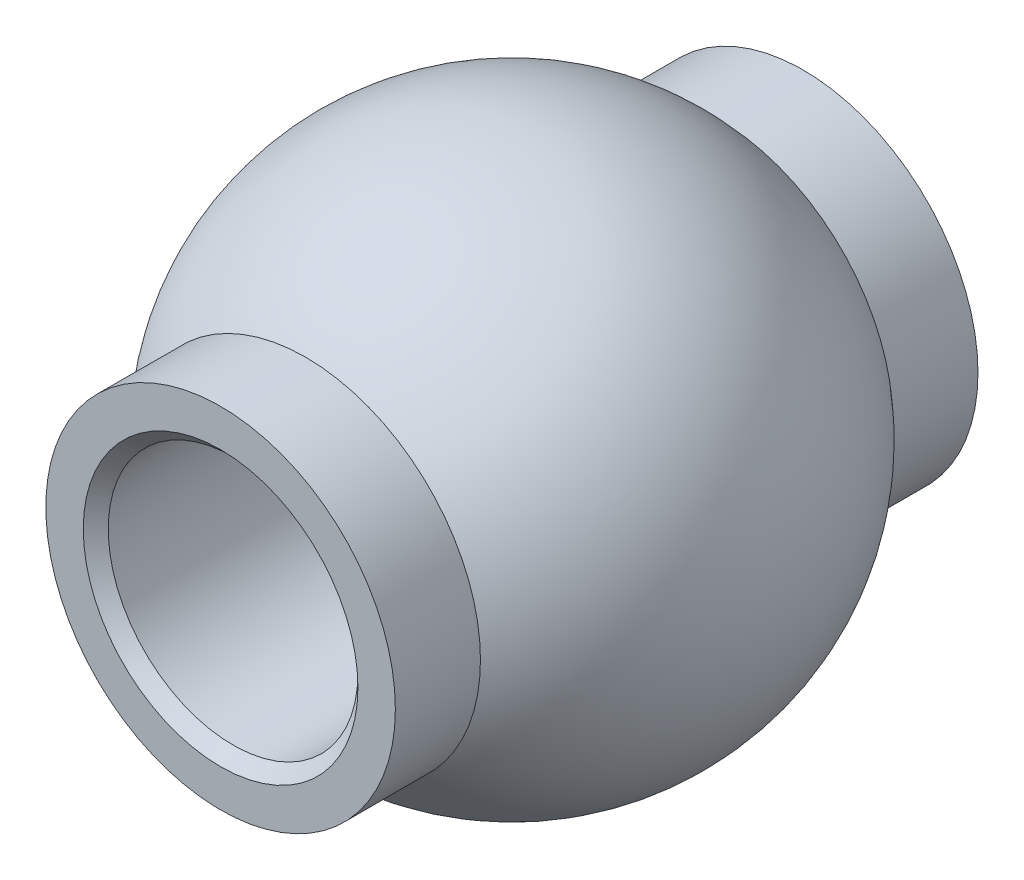
SolidWorks part; units mm, degrees
ref_plane "Front" through (0, 0, 0) normal (0, 0, 1) x (1, 0, 0)
ref_plane "Top" through (0, 0, 0) normal (0, 1, 0) x (1, 0, 0)
ref_plane "Right" through (0, 0, 0) normal (1, 0, 0) x (0, 0, -1)
sketch "Sketch1" plane through (0, 0, 0) normal (0, 0, 1) x (1, 0, 0)
  line L0 (0, 0) -> (0, -26.9875) construction
  line L1 (0, -26.9875) -> (4.7625, -26.9875) construction
  line L2 (4.7625, -26.9875) -> (4.7625, 0) construction
  line L3 (4.7625, 0) -> (0, 0) construction
  line L5 (0, 41.275) -> (0, 0) construction
  line L6 (0, 41.275) -> (14.2875, 41.275) construction
  line L7 (14.2875, 41.275) -> (14.2875, 26.9875) construction
  line L8 (-4.7625, -26.9875) -> (-4.7625, 0) construction
  line L9 (-8.7249, -26.9875) -> (8.7249, -26.9875) construction
  line L10 (8.7249, -26.9875) -> (8.7249, 10.0476) construction
  line L11 (-8.7249, -26.9875) -> (-8.7249, 10.0476) construction
  line L12 (4.8771, -26.9214) -> (4.8771, -27.9797) construction
  line L13 (4.8771, -27.9797) -> (3.9605, -27.4505) construction
  line L14 (3.9605, -27.4505) -> (4.8771, -26.9214) construction
  line L15 (3.9605, -27.4505) -> (4.0751, -27.4505) construction
  line L16 (4.8771, -27.4505) -> (4.7625, -27.4505) construction
  line L17 (4.0751, -27.5167) -> (4.0751, -27.3844) construction
  line L18 (4.7625, -27.9135) -> (4.7625, -26.9875) construction
  line L19 (4.8198, -27.9466) -> (4.8198, -26.9544) construction
  arc A0 (11.5062, 18.5176) -> (0, 41.275) centre (0, 26.9875) ccw construction
  circle A1 centre (0, 26.9875) radius 4.7625 construction
  circle A2 centre (0, 26.9875) radius 10.3124 construction
  circle A3 centre (0, 26.9875) radius 10.828 construction
  arc A4 (8.7249, 10.0476) -> (11.5062, 18.5176) centre (23.0124, 10.0476) cw construction
  point P16 (-4.7625, -16.0514)
  point P30 (4.0751, -27.4505)
  point P31 (-4.7625, -26.9875)
  point P33 (4.7625, -27.4505)
  point P36 (4.8198, -27.4505)
  point P37 (4.7625, -26.9875)
  dimension "Ball Dia" = 20.6248
  dimension "D1" = 21.656
  dimension "ID" = 9.525
  dimension "D2" = 10.9361
  dimension "body width" = 17.4498
  dimension "D4" = 26.9875
  dimension "Pitch" = 1.0583
  dimension "D5" = 0.1323
  dimension "Thread Dia" = 9.525
  dimension "Overall Width" = 28.575
  dimension "Shank Thread Length" = 26.9875
  dimension "Shank Center Length" = 53.975
sketch "Sketch2" plane through (0, 0, 0) normal (1, 0, 0) x (0, 0, -1)
  line L0 (11.1125, 26.9875) -> (-11.1125, 26.9875)
  line L1 (-11.1125, 22.225) -> (11.1125, 22.225)
  line L2 (0, 20.32) -> (0, 33.655)
  line L3 (0, 37.2999) -> (0, 16.6751) construction
  line L4 (0, 41.275) -> (0, 0) construction
  line L7 (11.1125, 33.655) -> (-11.1125, 33.655)
  line L8 (11.1125, 31.75) -> (-11.1125, 31.75)
  line L10 (11.1125, 20.32) -> (-11.1125, 20.32)
  line L11 (0, 26.9875) -> (-11.1125, 32.7723)
  line L12 (0, 26.9875) -> (-11.1125, 21.2027)
  circle A0 centre (0, 26.9875) radius 10.3124
  point P0 (0, 31.75)
  point P6 (0, 26.9875)
  point P9 (0, 26.9875)
  point P10 (0, 20.6375)
  point P16 (0, 31.75)
  point P17 (0, 33.655)
  point P23 (0, 20.6375)
  point P26 (0, 20.32)
  point P30 (0, 22.225)
  dimension "D2" = 20.6248
  dimension "Overall Width" = 22.225
  dimension "D1" = 13.335
  dimension "Maximum Ball Swivel" = 55
sketch "Sketch7" plane through (0, 0, 0) normal (0, 0, 1) x (1, 0, 0)
  line L0 (0, 37.2999) -> (0, 16.6751)
  line L1 (0, 41.275) -> (0, 0) construction
  line L2 (0, 0) -> (0, 16.6751) construction
  arc A0 (0, 16.6751) -> (0, 37.2999) centre (0, 26.9875) ccw
  circle A1 centre (0, 26.9875) radius 10.3124 construction
revolve "Revolve3" add sketch "Sketch7" angle 360 about L2
sketch "Sketch12" plane through (0, 0, 0) normal (0, 0, 1) x (1, 0, 0)
  circle A0 centre (0, 26.9875) radius 6.6675
  dimension "O" = 13.335
extrude "Extrude1" add sketch "Sketch12" against normal up to vertex (11.1125 mm away) and the other way up to vertex (11.1125 mm away) up to point (0, 26.9875, -11.1125) other way up to point (0, 26.9875, 11.1125)
sketch "Sketch10" plane through (0, 0, 0) normal (0, 0, 1) x (1, 0, 0)
  circle A0 centre (0, 26.9875) radius 4.7625 construction
  circle A1 centre (0, 26.9875) radius 4.7625
extrude "Cut-Extrude4" cut sketch "Sketch10" against normal through all and the other way through all
chamfer "Chamfer1" distance 0.4762 angle 45 2 edges at (4.7625, 26.9875, -11.1125) (4.7625, 26.9875, 11.1125)
sketch "Sketch13" plane through (0, 0, 0) normal (0, 0, 1) x (1, 0, 0)
  point P0 (0, 26.9875)
sketch "Sketch15" plane through (0, 0, 0) normal (1, 0, 0) x (0, 0, -1)
  line L0 (-7.867, 33.655) -> (-11.1125, 33.655)
  line L1 (-11.1125, 20.32) -> (-7.867, 20.32)
  line L3 (-7.867, 33.655) -> (-11.1125, 33.655)
  line L4 (-11.1125, 33.655) -> (-11.1125, 32.2262)
  line L5 (-11.1125, 21.7487) -> (-11.1125, 20.32)
  line L7 (-11.1125, 33.655) -> (-11.1125, 32.2262)
  line L8 (10.6362, 31.75) -> (-10.6363, 31.75)
  line L9 (-10.6363, 22.225) -> (10.6362, 22.225)
  line L11 (10.2876, 31.75) -> (-10.2876, 31.75)
  line L16 (11.1125, 33.655) -> (7.867, 33.655)
  line L17 (7.867, 20.32) -> (11.1125, 20.32)
  line L19 (11.1125, 33.655) -> (7.867, 33.655)
  line L20 (11.1125, 33.655) -> (11.1125, 32.2262)
  line L21 (11.1125, 21.7487) -> (11.1125, 20.32)
  line L23 (11.1125, 33.655) -> (11.1125, 32.2262)
  line L28 (-11.1125, 32.2262) -> (-10.2876, 31.75)
  line L29 (-7.867, 33.655) -> (-1.8407, 37.1343)
  line L30 (0, 26.9875) -> (0, 37.2999) construction
  line L31 (11.1125, 32.2262) -> (10.2876, 31.75)
  line L32 (7.867, 33.655) -> (1.8407, 37.1343)
  line L33 (-1.8407, 37.1343) -> (0, 37.2999)
  line L34 (0, 37.2999) -> (1.8407, 37.1343)
  dimension "D1" = 120
  dimension "D2" = 30
sketch "Sketch16" plane through (0, 0, 0) normal (1, 0, 0) x (0, 0, -1)
  line L0 (-7.867, 33.655) -> (-11.1125, 33.655)
  line L1 (-11.1125, 20.32) -> (-7.867, 20.32)
  line L2 (-11.1125, 20.32) -> (-7.867, 20.32)
  line L3 (-7.867, 33.655) -> (-11.1125, 33.655)
  line L4 (-11.1125, 33.655) -> (-11.1125, 32.2262)
  line L5 (-11.1125, 21.7487) -> (-11.1125, 20.32)
  line L6 (-11.1125, 21.7487) -> (-11.1125, 20.32)
  line L7 (-11.1125, 33.655) -> (-11.1125, 32.2262)
  line L8 (10.6362, 31.75) -> (-10.6363, 31.75)
  line L9 (-10.6363, 22.225) -> (10.6362, 22.225)
  line L10 (-10.6363, 22.225) -> (10.6362, 22.225)
  line L11 (10.6362, 31.75) -> (-10.6363, 31.75)
  line L12 (-11.1125, 32.2262) -> (-10.6363, 31.75)
  line L13 (-10.6363, 22.225) -> (-11.1125, 21.7487)
  line L14 (-10.6363, 22.225) -> (-11.1125, 21.7487)
  line L15 (-11.1125, 32.2262) -> (-10.6363, 31.75)
  line L16 (11.1125, 33.655) -> (7.867, 33.655)
  line L17 (7.867, 20.32) -> (11.1125, 20.32)
  line L18 (7.867, 20.32) -> (11.1125, 20.32)
  line L19 (11.1125, 33.655) -> (7.867, 33.655)
  line L20 (11.1125, 21.7487) -> (10.6362, 22.225)
  line L21 (10.6362, 31.75) -> (11.1125, 32.2262)
  line L22 (10.6362, 31.75) -> (11.1125, 32.2262)
  line L23 (11.1125, 21.7487) -> (10.6362, 22.225)
  line L24 (11.1125, 33.655) -> (11.1125, 32.2262)
  line L25 (11.1125, 21.7487) -> (11.1125, 20.32)
  line L26 (11.1125, 21.7487) -> (11.1125, 20.32)
  line L27 (11.1125, 33.655) -> (11.1125, 32.2262)
  line L28 (-7.867, 33.655) -> (0, 37.2999)
  line L29 (0, 37.2999) -> (7.867, 33.655)
  arc A0 (7.867, 33.655) -> (-7.867, 33.655) centre (0, 26.9875) ccw
  arc A1 (-7.867, 20.32) -> (7.867, 20.32) centre (0, 26.9875) ccw
  arc A2 (-7.867, 20.32) -> (7.867, 20.32) centre (0, 26.9875) ccw
equation "\"D1@Sketch1\"=\"Ball Dia@Sketch1\"*1.05"
equation "\"D1@Chamfer1\" = \"ID@Sketch1\" / 20"
equation "\"O@Sketch12\"= \"ID@Sketch1\" * 1.4"
equation "\"D5@Sketch1\" = \"Pitch@Sketch1\" / 8"
equation "\"D1@Sketch2\"=\"ID@Sketch1\"*1.4"
equation "\"D2@Sketch2\"= \"Ball Dia@Sketch1\""
